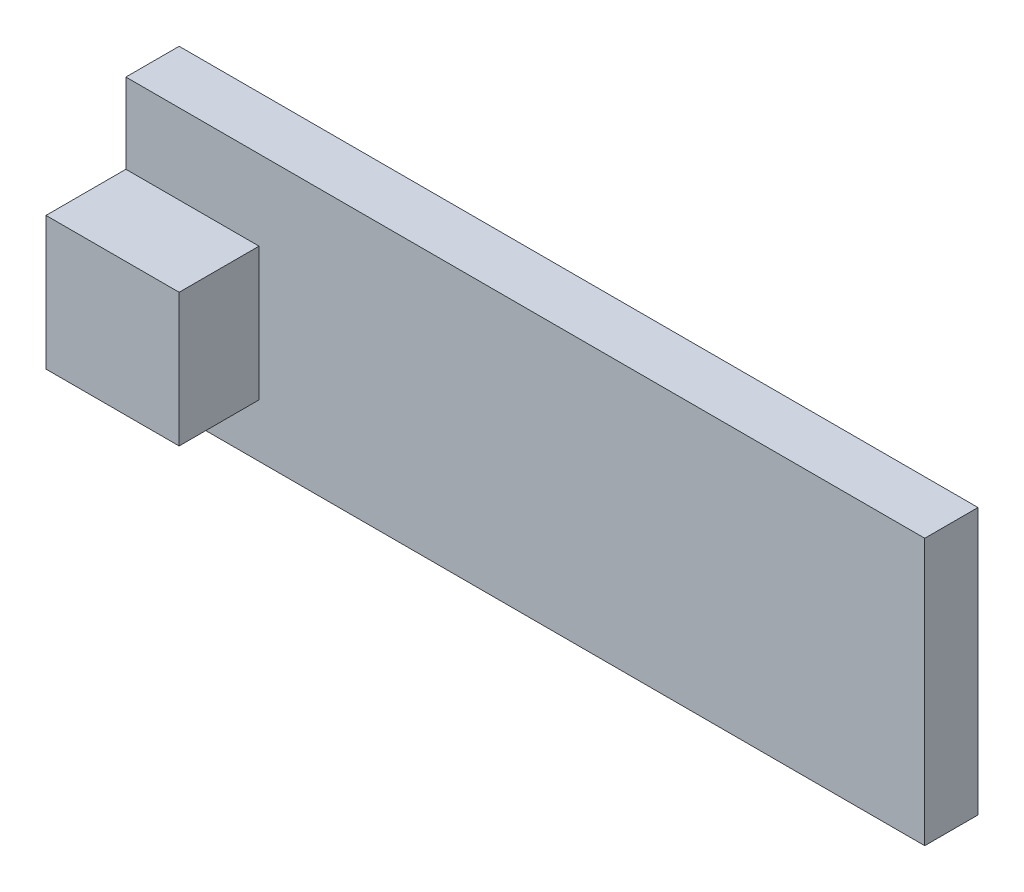
SolidWorks part; units mm, degrees
ref_plane "前视基准面" through (0, 0, 0) normal (0, 0, 1) x (1, 0, 0)
ref_plane "上视基准面" through (0, 0, 0) normal (0, 1, 0) x (1, 0, 0)
ref_plane "右视基准面" through (0, 0, 0) normal (1, 0, 0) x (0, 0, -1)
sketch "草图1" plane through (0, 0, 0) normal (0, 0, 1) x (1, 0, 0)
  line L1 (0, 0) -> (30, 0)
  line L2 (0, 0) -> (0, 10)
  line L3 (0, 10) -> (30, 10)
  line L4 (30, 0) -> (30, 10)
  dimension "D1" = 30
  dimension "D2" = 10
extrude "凸台-拉伸1" add sketch "草图1" along normal blind 2
sketch "草图2" plane through (0, 0, 2) normal (0, 0, 1) x (1, 0, 0)
  line L0 (0, 10) -> (0, 0) construction
  line L1 (5, 7) -> (0, 7)
  line L2 (5, 7) -> (5, 2)
  line L3 (5, 2) -> (0, 2)
  line L4 (0, 7) -> (0, 2)
  line L5 (30, 10) -> (0, 10) construction
  dimension "D1" = 3
  dimension "D2" = 5
  dimension "D3" = 5
extrude "凸台-拉伸2" add sketch "草图2" along normal blind 3 separate body
